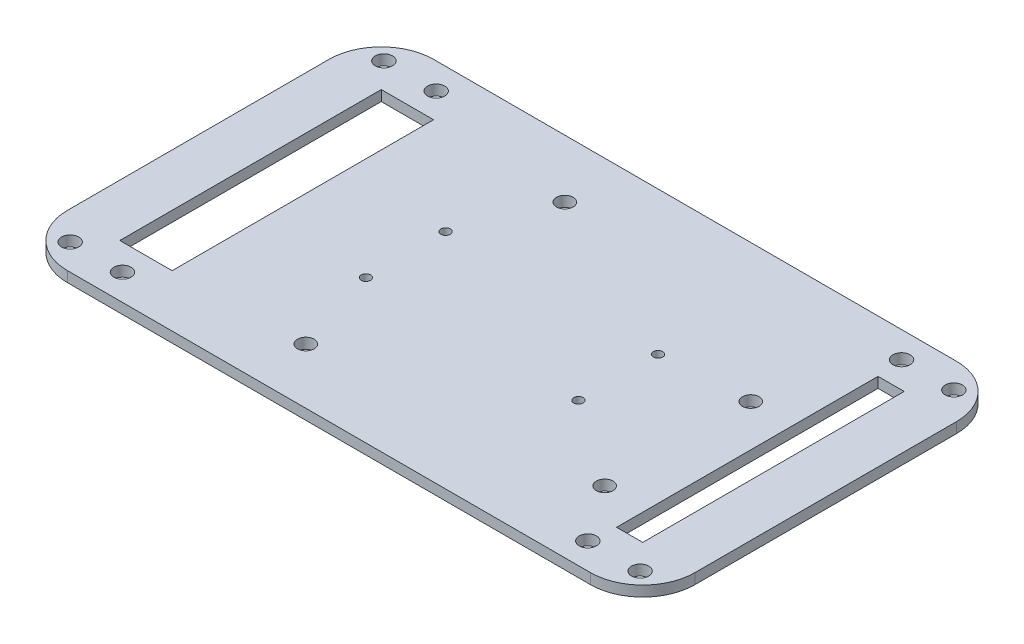
SolidWorks part; units mm, degrees
ref_plane "Alzado" through (0, 0, 0) normal (0, 0, 1) x (1, 0, 0)
ref_plane "Planta" through (0, 0, 0) normal (0, 1, 0) x (1, 0, 0)
ref_plane "Vista lateral" through (0, 0, 0) normal (1, 0, 0) x (0, 0, -1)
sketch "PlantaIceZum" plane through (0, 0, 0) normal (0, 1, 0) x (1, 0, 0)
  line L1 (0, 0) -> (120, 0)
  line L2 (0, 0) -> (0, 70)
  line L3 (0, 70) -> (120, 70)
  line L4 (120, 0) -> (120, 70)
  circle A0 centre (97, 43.66) radius 1.6
  circle A1 centre (46.2, 58.9) radius 1.6
  circle A2 centre (44.93, 10.64) radius 1.6
  circle A3 centre (97, 15.72) radius 1.6
  dimension "D3" = 50.8
  dimension "D5" = 27.94
  dimension "D6" = 52.07
  dimension "D7" = 3.2
  dimension "D8" = 5.08
  dimension "D1" = 70
  dimension "D2" = 120
  dimension "D4" = 15.24
  dimension "D9" = 11.1
  dimension "D10" = 23
extrude "Saliente-Extruir3" add sketch "PlantaIceZum" along normal blind 2
fillet "Redondeo1" radius 10 1 edges at (0, 1, 0)
fillet "Redondeo2" radius 10 1 edges at (0, 1, -70)
fillet "Redondeo3" radius 10 1 edges at (120, 1, -70)
fillet "Redondeo4" radius 10 1 edges at (120, 1, 0)
sketch "Croquis1" plane through (0, 2, 0) normal (0, 1, 0) x (1, 0, 0)
  line L0 (110, 70) -> (10, 70) construction
  line L1 (20, 60) -> (10, 60)
  line L2 (20, 60) -> (20, 10)
  line L3 (20, 10) -> (10, 10)
  line L4 (10, 60) -> (10, 10)
  line L5 (10, 0) -> (110, 0) construction
  line L6 (0, 60) -> (0, 10) construction
  line L7 (110, 60) -> (105, 60)
  line L8 (110, 60) -> (110, 10)
  line L9 (110, 10) -> (105, 10)
  line L10 (105, 60) -> (105, 10)
  line L11 (120, 10) -> (120, 60) construction
  dimension "D1" = 10
  dimension "D2" = 10
  dimension "D3" = 10
  dimension "D4" = 10
  dimension "D5" = 5
  dimension "D6" = 10
  dimension "D7" = 10
  dimension "D8" = 10
extrude "Cortar-Extruir1" cut sketch "Croquis1" against normal blind 5
sketch "Croquis4" plane through (0, 2, 0) normal (0, 1, 0) x (1, 0, 0)
  circle A0 centre (5.5, 65) radius 1.65
  circle A1 centre (114.5, 65) radius 1.65
  circle A2 centre (5.5, 5) radius 1.65
  circle A3 centre (114.5, 5) radius 1.65
  arc A4 (10, 70) -> (0, 60) centre (10, 60) ccw construction
  arc A5 (120, 60) -> (110, 70) centre (110, 60) ccw construction
  arc A6 (110, 0) -> (120, 10) centre (110, 10) ccw construction
  circle A7 centre (15.5, 65) radius 1.65
  arc A8 (0, 10) -> (10, 0) centre (10, 10) ccw construction
  circle A9 centre (104.5, 65) radius 1.65
  circle A10 centre (15.5, 5) radius 1.65
  circle A11 centre (104.5, 5) radius 1.65
  point P13 (2.9289, 67.0711)
  point P17 (117.0711, 67.0711)
  point P21 (117.0711, 2.9289)
  point P23 (2.9289, 2.9289)
  dimension "D5" = 3.3
  dimension "D6" = 3.3
  dimension "D3" = 3.3
  dimension "D7" = 3.3
  dimension "D13" = 3.3
  dimension "D14" = 3.3
  dimension "D15" = 3.3
  dimension "D16" = 3.3
  dimension "D1" = 109
  dimension "D2" = 60
  dimension "D4" = 3.3015
  dimension "D8" = 109
  dimension "D9" = 3.3015
  dimension "D10" = 3.3015
  dimension "D11" = 3.3015
  dimension "D12" = 60
  dimension "D17" = 10
  dimension "D18" = 10
  dimension "D19" = 10
  dimension "D20" = 10
extrude "Cortar-Extruir2" cut sketch "Croquis4" against normal blind 5
sketch "Croquis6" plane through (0, 2, 0) normal (0, 1, 0) x (1, 0, 0)
  circle A0 centre (39.68, 42.62) radius 0.9
  circle A1 centre (39.68, 27.38) radius 0.9
  circle A2 centre (80.32, 42.62) radius 0.9
  circle A3 centre (80.32, 27.38) radius 0.9
  dimension "D1" = 1.8
  dimension "D2" = 1.8
  dimension "D3" = 1.8
  dimension "D4" = 1.8
  dimension "D5" = 15.24
  dimension "D6" = 40.64
  dimension "D7" = 29.68
  dimension "D8" = 17.38
extrude "Cortar-Extruir4" cut sketch "Croquis6" against normal blind 10
